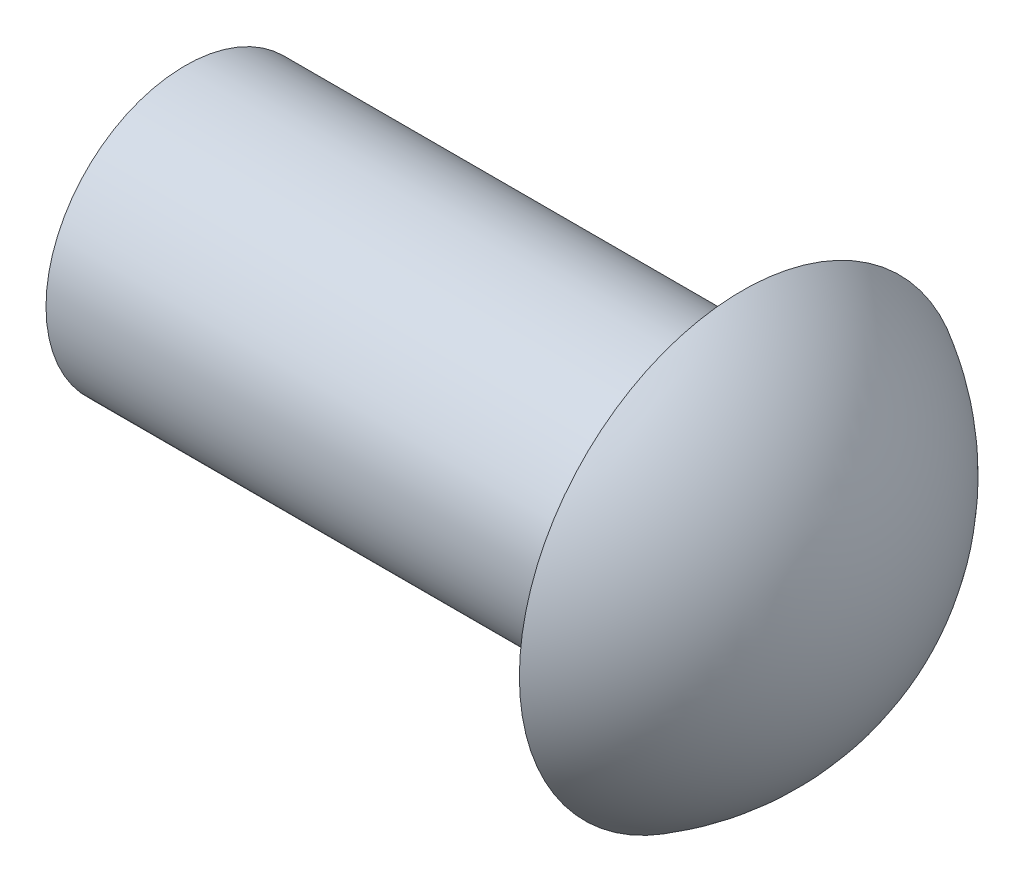
SolidWorks part; units mm, degrees
ref_plane "Front Plane" through (0, 0, 0) normal (0, 0, 1) x (1, 0, 0)
ref_plane "Top Plane" through (0, 0, 0) normal (0, 1, 0) x (1, 0, 0)
ref_plane "Right Plane" through (0, 0, 0) normal (1, 0, 0) x (0, 0, -1)
sketch "Sketch1" plane through (0, 0, 0) normal (0, 1, 0) x (1, 0, 0)
  line L0 (0, 0) -> (0, 7.5)
  line L1 (0, 7.5) -> (30, 7.5)
  line L2 (30, 7.5) -> (30, 12)
  line L3 (0, 0) -> (37, 0) construction
  line L4 (0, 0) -> (37, 0)
  arc A0 (30, 12) -> (37, 0) centre (23.2143, 0) cw
  point P7 (21.9744, 0)
  point P8 (0, 0)
  dimension "D1" = 7.5
  dimension "D2" = 30
  dimension "D3" = 7
  dimension "D4" = 4.5
revolve "Revolve1" add sketch "Sketch1" angle 360 about L3
